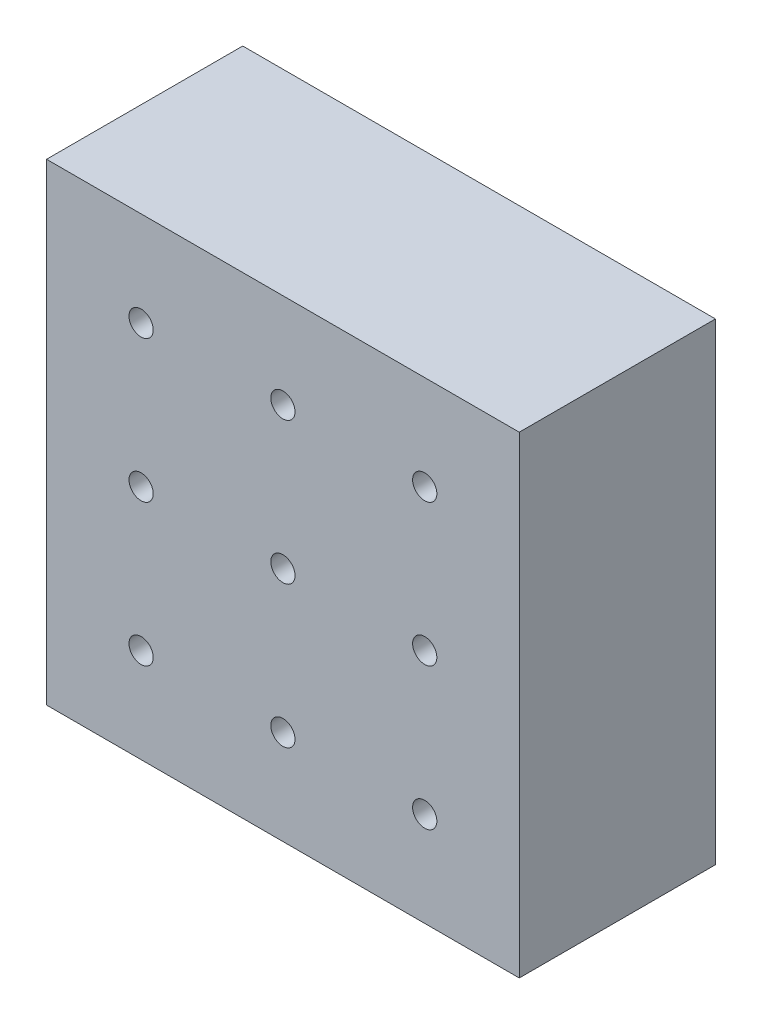
SolidWorks part; units mm, degrees
ref_plane "Front Plane" through (0, 0, 0) normal (1, 0, 0) x (0, 1, 0)
ref_plane "Top Plane" through (0, 0, 0) normal (0, 0, 1) x (0, 1, 0)
ref_plane "Right Plane" through (0, 0, 0) normal (0, 1, 0) x (-1, 0, 0)
sketch "Sketch1" plane through (0, 0, 0) normal (0, 0, 1) x (0, 1, 0)
  line L5 (-8, 32) -> (32, 32)
  line L6 (-8, 32) -> (-8, -8)
  line L7 (-8, -8) -> (32, -8)
  line L8 (32, 32) -> (32, -8)
  line L9 (-8, 32) -> (32, -8) construction
  line L10 (-8, -8) -> (32, 32) construction
  circle A0 centre (0, 0) radius 4.55
  circle A1 centre (12, 0) radius 4.55
  circle A2 centre (24, 0) radius 4.55
  circle A3 centre (12, 12) radius 4.55
  circle A4 centre (24, 12) radius 4.55
  circle A5 centre (12, 24) radius 4.55
  circle A6 centre (24, 24) radius 4.55
  circle A7 centre (0, 12) radius 4.55
  circle A8 centre (0, 24) radius 4.55
  point P0 (0, 0)
  dimension "D1" = 9.1
  dimension "D4" = 40
  dimension "D5" = 40
  dimension "D2" = 3
  dimension "D3" = 3
extrude "Boss-Extrude1" add sketch "Sketch1" along normal blind 1.6
sketch "Sketch2" plane through (0, 0, 1.6) normal (0, 0, 1) x (1, 0, 0)
  line L1 (-32, 32) -> (8, 32)
  line L2 (-32, 32) -> (-32, -8)
  line L3 (-32, -8) -> (8, -8)
  line L4 (8, 32) -> (8, -8)
  line L5 (-32, 32) -> (8, -8) construction
  line L6 (-32, -8) -> (8, 32) construction
  circle A0 centre (0, 0) radius 1.025
  circle A1 centre (-12, 0) radius 1.025
  circle A2 centre (-24, 0) radius 1.025
  circle A3 centre (-12, 12) radius 1.025
  circle A4 centre (-24, 12) radius 1.025
  circle A5 centre (-12, 24) radius 1.025
  circle A6 centre (-24, 24) radius 1.025
  circle A7 centre (0, 12) radius 1.025
  circle A8 centre (0, 24) radius 1.025
  dimension "D1" = 2.05
  dimension "D2" = 3
extrude "Boss-Extrude2" add sketch "Sketch2" along normal blind 15
